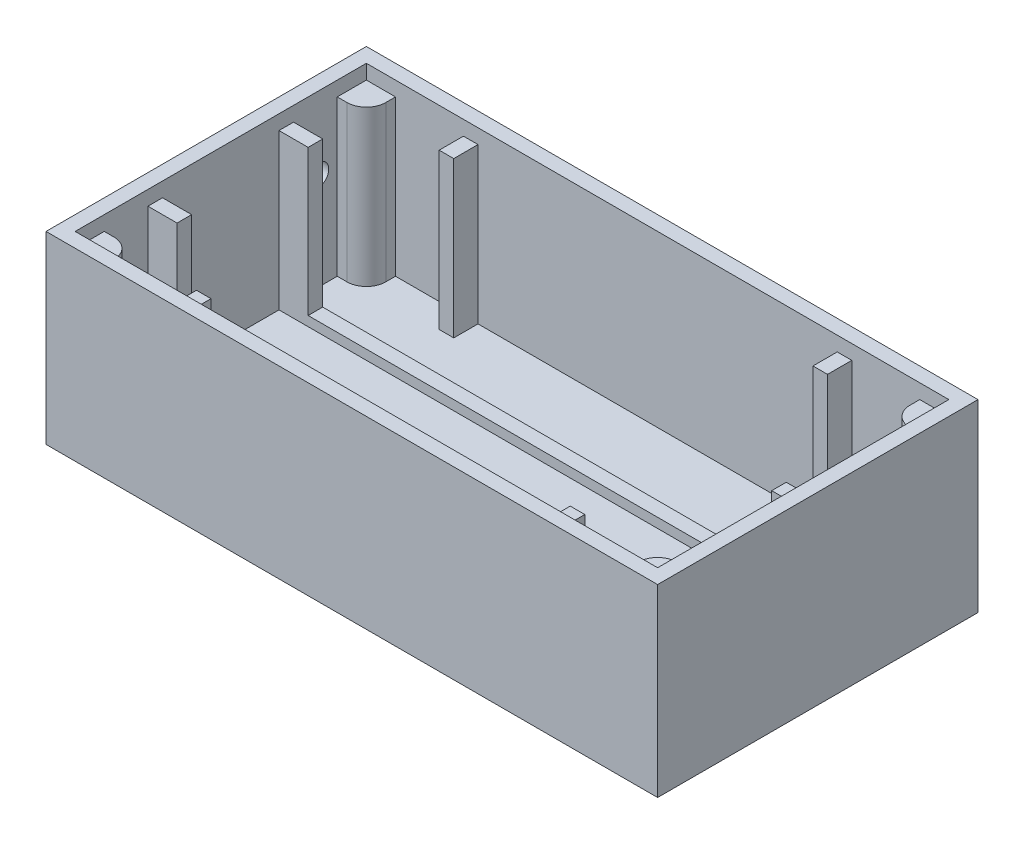
SolidWorks part; units mm, degrees
ref_plane "Спереди" through (0, 0, 0) normal (0, 0, 1) x (1, 0, 0)
ref_plane "Сверху" through (0, 0, 0) normal (0, 1, 0) x (1, 0, 0)
ref_plane "Справа" through (0, 0, 0) normal (1, 0, 0) x (0, 0, -1)
sketch "Эскиз3" plane through (0, 0, 0) normal (0, 1, 0) x (1, 0, 0)
  line L0 (0, 0) -> (126, 0)
  line L1 (0, 0) -> (0, 66)
  line L2 (126, 0) -> (126, 66)
  line L3 (0, 66) -> (126, 66)
  line L4 (3, 3) -> (123, 3)
  line L5 (3, 3) -> (3, 63)
  line L6 (123, 3) -> (123, 63)
  line L7 (3, 63) -> (123, 63)
  line L8 (63, 66) -> (63, 0) construction
  line L9 (126, 33) -> (0, 33) construction
  point P13 (63, 63)
  point P14 (123, 33)
  dimension "D1" = 3
  dimension "D2" = 3
  dimension "D3" = 120
  dimension "D4" = 60
extrude "Бобышка-Вытянуть2" add sketch "Эскиз3" along normal blind 35
sketch "Эскиз4" plane through (0, 35, 0) normal (0, 1, 0) x (1, 0, 0)
  line L0 (3, 18) -> (9, 18)
  line L1 (3, 18) -> (3, 21)
  line L2 (9, 18) -> (9, 21)
  line L3 (3, 21) -> (9, 21)
  line L4 (3, 63) -> (3, 3) construction
  line L5 (3, 45) -> (9, 45)
  line L6 (3, 45) -> (3, 48)
  line L7 (9, 45) -> (9, 48)
  line L8 (3, 48) -> (9, 48)
  line L9 (3, 33) -> (123, 33) construction
  line L10 (123, 3) -> (123, 63) construction
  line L11 (3, 21) -> (3, 45) construction
  line L12 (123, 31.5) -> (123, 34.5)
  line L13 (123, 31.5) -> (118, 31.5)
  line L14 (123, 34.5) -> (118, 34.5)
  line L15 (118, 31.5) -> (118, 34.5)
  line L16 (63, 63) -> (63, 3) construction
  line L17 (123, 63) -> (3, 63) construction
  line L18 (3, 3) -> (123, 3) construction
  line L19 (23, 63) -> (26, 63)
  line L20 (23, 63) -> (23, 58)
  line L21 (26, 63) -> (26, 58)
  line L22 (23, 58) -> (26, 58)
  line L23 (100, 63) -> (103, 63)
  line L24 (100, 63) -> (100, 58)
  line L25 (103, 63) -> (103, 58)
  line L26 (100, 58) -> (103, 58)
  line L27 (26, 63) -> (100, 63) construction
  line L28 (100, 8) -> (103, 8)
  line L29 (103, 3) -> (103, 8)
  line L30 (100, 3) -> (100, 8)
  line L31 (100, 3) -> (103, 3)
  line L32 (23, 8) -> (26, 8)
  line L33 (26, 3) -> (26, 8)
  line L34 (23, 3) -> (23, 8)
  line L35 (23, 3) -> (26, 3)
  point P14 (3, 33)
  dimension "D1" = 3
  dimension "D2" = 30
  dimension "D3" = 6
  dimension "D4" = 5
  dimension "D5" = 5
  dimension "D6" = 80
extrude "Бобышка-Вытянуть3" add sketch "Эскиз4" against normal up to surface (35 mm away) up to face at (63, 0, -33)
sketch "Эскиз5" plane through (0, 35, 0) normal (0, 1, 0) x (1, 0, 0)
  line L0 (100, 63) -> (26, 63) construction
  line L1 (123, 63) -> (3, 63)
  line L2 (3, 45) -> (3, 21) construction
  line L3 (3, 63) -> (3, 3)
  line L4 (26, 3) -> (100, 3) construction
  line L5 (3, 3) -> (123, 3)
  line L6 (123, 3) -> (123, 31.5) construction
  line L7 (123, 3) -> (123, 63)
extrude "Вырез-Вытянуть1" cut sketch "Эскиз5" against normal blind 3
sketch "Эскиз6" plane through (0, 0, 0) normal (0, -1, 0) x (1, 0, 0)
  line L0 (3, -63) -> (9, -63)
  line L1 (3, -63) -> (3, -57)
  line L2 (9, -63) -> (9, -61)
  line L3 (3, -57) -> (5, -57)
  line L4 (23, -63) -> (3, -63) construction
  line L5 (0, -33) -> (126, -33) construction
  line L6 (0, -66) -> (0, 0) construction
  line L7 (126, 0) -> (126, -66) construction
  line L8 (63, 0) -> (63, -66) construction
  line L9 (0, 0) -> (126, 0) construction
  line L10 (126, -66) -> (0, -66) construction
  line L11 (3, -9) -> (5, -9)
  line L12 (9, -3) -> (9, -5)
  line L13 (3, -3) -> (3, -9)
  line L14 (3, -3) -> (9, -3)
  line L15 (123, -3) -> (117, -3)
  line L16 (123, -3) -> (123, -9)
  line L17 (117, -3) -> (117, -5)
  line L18 (123, -9) -> (121, -9)
  line L19 (123, -57) -> (121, -57)
  line L20 (117, -63) -> (117, -61)
  line L21 (123, -63) -> (123, -57)
  line L22 (123, -63) -> (117, -63)
  arc A0 (9, -61) -> (5, -57) centre (5, -61) ccw
  arc A1 (9, -5) -> (5, -9) centre (5, -5) cw
  arc A2 (117, -5) -> (121, -9) centre (121, -5) ccw
  arc A3 (117, -61) -> (121, -57) centre (121, -61) cw
  point P9 (9, -57)
  point P28 (9, -9)
  point P41 (117, -9)
  point P42 (117, -57)
  dimension "D2" = 4
  dimension "D1" = 6
extrude "Бобышка-Вытянуть4" add sketch "Эскиз6" against normal up to surface (32 mm away) up to face at (6, 32, -46.5)
sketch "Эскиз7" plane through (0, 0, 0) normal (0, -1, 0) x (1, 0, 0)
  line L4 (0, 0) -> (0, -66)
  line L5 (0, -66) -> (126, -66)
  line L6 (126, -66) -> (126, 0)
  line L7 (126, 0) -> (0, 0)
  line L8 (0, 0) -> (0, -66)
  line L9 (0, -66) -> (126, -66)
  line L10 (126, -66) -> (126, 0)
  line L11 (126, 0) -> (0, 0)
  dimension "D1" = 0
extrude "Бобышка-Вытянуть5" add sketch "Эскиз7" along normal blind 3
sketch "Эскиз8" plane through (9, 0, 0) normal (1, 0, 0) x (0, 0, -1)
  line L0 (18, 2) -> (21, 2)
  line L1 (45, 2) -> (48, 2)
  line L4 (21, 0) -> (21, 32)
  line L5 (21, 32) -> (18, 32)
  line L6 (18, 32) -> (18, 0)
  line L7 (18, 0) -> (21, 0)
  line L8 (21, 0) -> (21, 2)
  line L10 (18, 2) -> (18, 0)
  line L11 (18, 0) -> (21, 0)
  line L12 (48, 0) -> (48, 32)
  line L13 (48, 32) -> (45, 32)
  line L14 (45, 32) -> (45, 0)
  line L15 (45, 0) -> (48, 0)
  line L16 (48, 0) -> (48, 2)
  line L18 (45, 2) -> (45, 0)
  line L19 (45, 0) -> (48, 0)
  dimension "D3" = 2
  dimension "D1" = 0
  dimension "D2" = 0
extrude "Бобышка-Вытянуть6" add sketch "Эскиз8" along normal up to surface (114 mm away) up to face at (123, 21.8333, -33)
sketch "Эскиз9" plane through (0, -3, 0) normal (0, -1, 0) x (1, 0, 0)
  line L0 (0, -33) -> (126, -33) construction
  line L1 (0, 0) -> (0, -66) construction
  line L2 (126, -66) -> (126, 0) construction
ref_plane "SymCase" through (0, 0, -33) normal (0, 0, -1) x (1, 0, 0)
sketch "Эскиз10" plane through (0, 0, 0) normal (-1, 0, 0) x (0, 0, 1)
  line L0 (-33, 35) -> (-33, -3) construction
  line L1 (-66, 35) -> (0, 35) construction
  line L2 (-53, 20) -> (-13, 20) construction
  circle A0 centre (-53, 20) radius 2.25
  circle A1 centre (-13, 20) radius 2.25
  point P7 (-33, 20)
  dimension "D3" = 4.5
  dimension "D4" = 4.5
  dimension "D1" = 40
  dimension "D2" = 15
extrude "Вырез-Вытянуть2" cut sketch "Эскиз10" against normal up to surface (3 mm away) up to face at (3, 20.375, -33)
